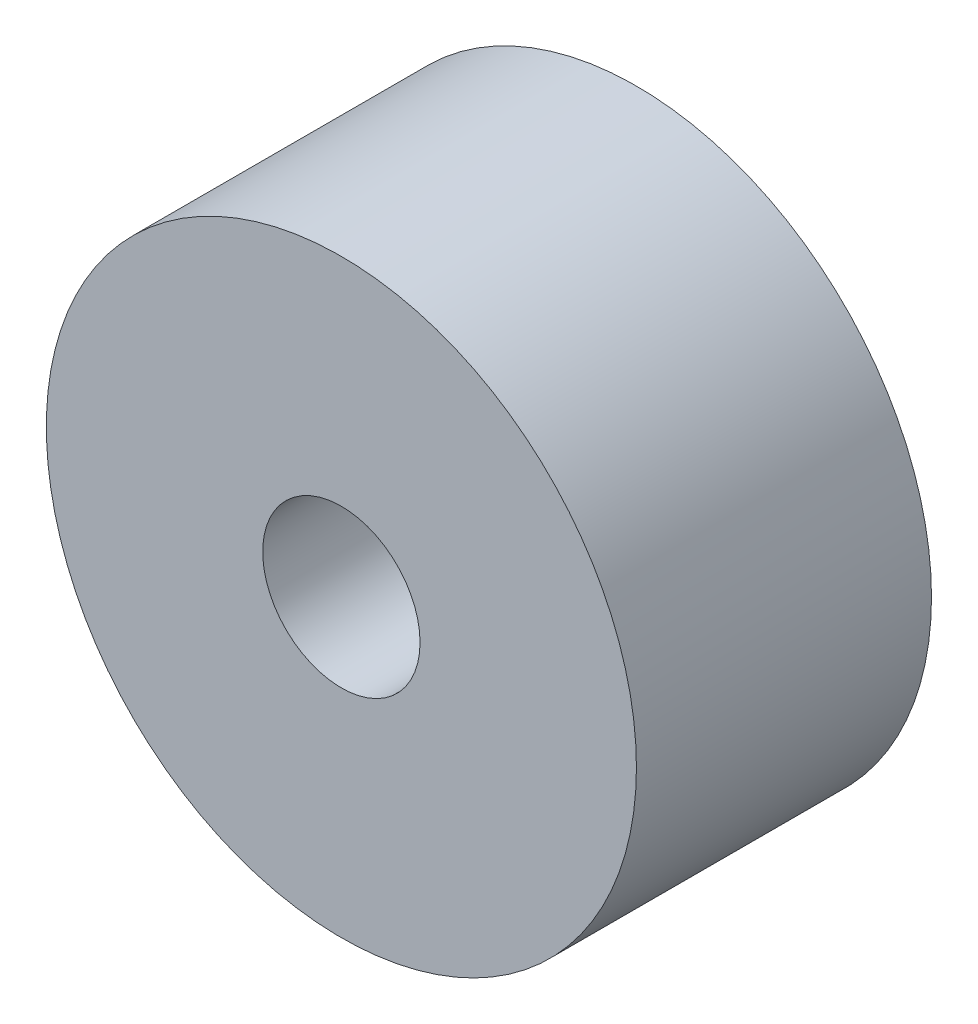
SolidWorks part; units mm, degrees
other "缓冲块" parameters "D1"=126.1723, "D2"=72.3629
ref_plane "前视基准面" through (0, 0, 0) normal (0, 0, 1) x (1, 0, 0)
ref_plane "上视基准面" through (0, 0, 0) normal (0, 1, 0) x (1, 0, 0)
ref_plane "右视基准面" through (0, 0, 0) normal (1, 0, 0) x (0, 0, -1)
other "Configuration Table"
sketch "草图1" plane through (0, 0, 0) normal (0, 0, 1) x (1, 0, 0)
  circle A0 centre (0, 0) radius 30
  circle A1 centre (0, 0) radius 8
  dimension "D1" = 60
  dimension "D2" = 16
extrude "凸台-拉伸1" add sketch "草图1" along normal blind 30
equation "\"缓冲块外径\" = 60"
equation "\"缓冲块内孔\" = \"活塞杆直径\" + 2*\"间隙\""
equation "\"缓冲块自由高\" = 30"
equation "\"D2@草图1\"=\"缓冲块内孔\""
equation "\"D1@草图1\"=\"缓冲块外径\""
equation "\"D1@凸台-拉伸1\"=\"缓冲块自由高\""
